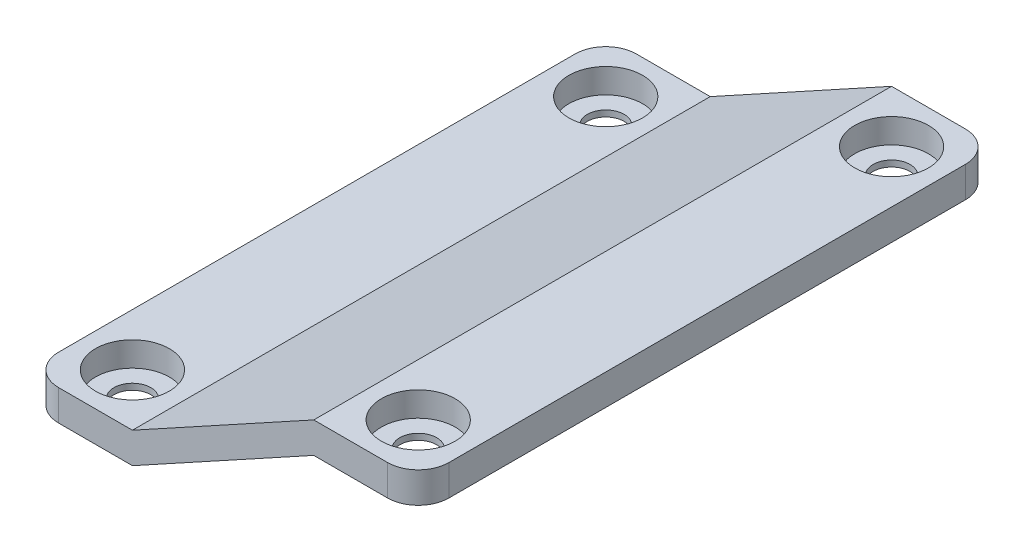
SolidWorks part; units mm, degrees
ref_plane "Front Plane" through (0, 0, 0) normal (0, 0, 1) x (1, 0, 0)
ref_plane "Top Plane" through (0, 0, 0) normal (0, 1, 0) x (1, 0, 0)
ref_plane "Right Plane" through (0, 0, 0) normal (1, 0, 0) x (0, 0, -1)
sketch "Sketch1" plane through (0, 0, 0) normal (0, 0, 1) x (1, 0, 0)
  line L0 (-15.0078, -4.569) -> (14.4922, 11.631)
  line L1 (-15.0078, -9.569) -> (-32.0078, -9.569)
  line L2 (-15.0078, -4.569) -> (-32.0078, -4.569)
  line L3 (-32.0078, -9.569) -> (-32.0078, -4.569)
  line L4 (14.4922, 6.631) -> (31.4922, 6.631)
  line L5 (14.4922, 11.631) -> (31.4922, 11.631)
  line L6 (31.4922, 6.631) -> (31.4922, 11.631)
  line L7 (-15.0078, -9.569) -> (14.4922, 6.631)
extrude "Cover Body" add sketch "Sketch1" against normal blind 94
sketch "Screw Hole outlines" plane through (0, -4.569, 0) normal (0, 1, 0) x (1, 0, 0)
  line L0 (14.4922, 94) -> (-15.0078, 94) construction
  line L1 (-23.5078, 85.5) -> (22.9922, 85.5) construction
  line L2 (-23.5078, 85.5) -> (-23.5078, 8.5) construction
  line L3 (-23.5078, 8.5) -> (22.9922, 8.5) construction
  line L4 (22.9922, 85.5) -> (22.9922, 8.5) construction
  line L6 (31.4922, 94) -> (31.4922, 0) construction
  dimension "D1" = 8.5
  dimension "D2" = 8.5
hole_wizard "CBORE for M6 Hex Head Bolt1" positions "Sketch2" profile "Sketch4" counterbore size "M6" standard "ANSI Metric" end condition through all
sketch "Sketch2" plane through (0, -4.569, 0) normal (0, 1, 0) x (1, 0, 0)
  point P0 (-23.5078, 85.5)
  point P3 (-23.5078, 8.5)
sketch "Sketch4" plane through (-23.5078, -4.569, -85.5) normal (1, 0, 0) x (0, 0, 1)
  line L0 (0, 0) -> (0, 5)
  line L1 (0, 5) -> (3, 5)
  line L3 (3, 5) -> (3, 4)
  line L4 (3, 4) -> (6, 4)
  line L5 (6, 4) -> (6, 0)
  line L7 (6, 0) -> (0, 0)
  line L11 (0, -6.35) -> (0, 107.95) construction
  dimension "Thru Hole Dia." = 6
  dimension "Thru Hole Depth" = 5
  dimension "C'Bore Dia." = 12
  dimension "C'Bore Depth" = 4
ref_plane "Upper Lid Plane" through (22.9922, 0, 0) normal (1, 0, 0) x (0, 0, -1)
sketch "Sketch9" plane through (22.9922, 0, 0) normal (1, 0, 0) x (0, 0, -1)
  line L0 (8.5, -4.569) -> (8.5, 11.631) construction
  line L1 (85.5, -4.569) -> (8.5, -4.569) construction
  line L2 (85.5, -4.569) -> (8.5, -4.569) construction
  line L3 (94, 11.631) -> (0, 11.631) construction
  line L4 (85.5, -4.569) -> (85.5, 11.631) construction
hole_wizard "CBORE for M6 Hex Head Bolt2" positions "Sketch10" profile "Sketch11" counterbore size "M6" standard "ANSI Metric" end condition up to next
sketch "Sketch10" plane through (0, 11.631, 0) normal (0, 1, 0) x (1, 0, 0)
  point P0 (22.9922, 8.5)
  point P3 (22.9922, 85.5)
sketch "Sketch11" plane through (22.9922, 11.631, -8.5) normal (1, 0, 0) x (0, 0, 1)
  line L0 (0, 0) -> (0, 5)
  line L1 (0, 5) -> (3, 5)
  line L3 (3, 5) -> (3, 4)
  line L4 (3, 4) -> (6, 4)
  line L5 (6, 4) -> (6, 0)
  line L7 (6, 0) -> (0, 0)
  line L11 (0, -6.35) -> (0, 107.95) construction
  dimension "Thru Hole Dia." = 6
  dimension "Thru Hole Depth" = 5
  dimension "C'Bore Dia." = 12
  dimension "C'Bore Depth" = 4
fillet "Fillet1" radius 5 4 edges at (-32.0078, -7.069, -94) (31.4922, 9.131, -94) (31.4922, 9.131, 0) (-32.0078, -7.069, 0)
